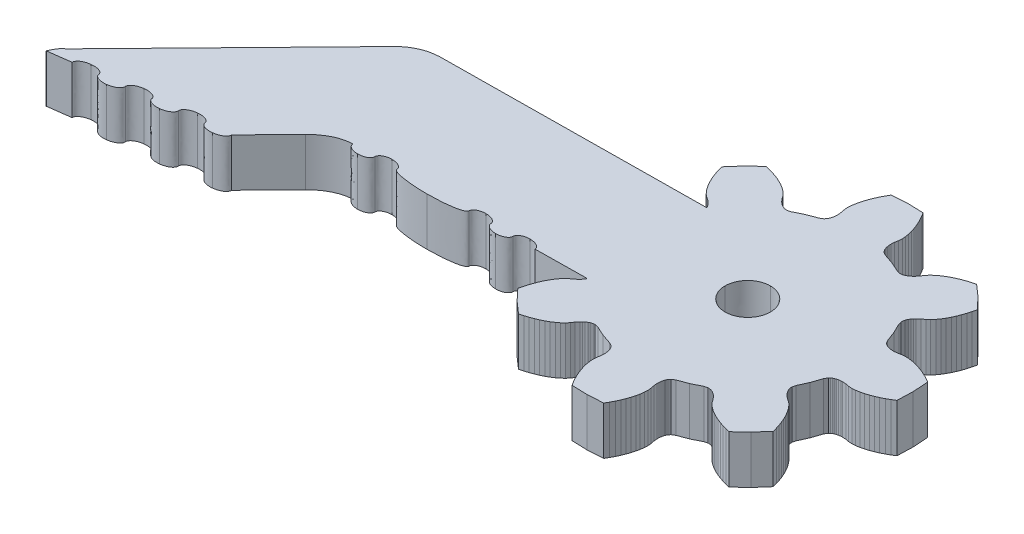
SolidWorks part; units mm, degrees
ref_plane "Front Plane" through (0, 0, 0) normal (0, 0, 1) x (1, 0, 0)
ref_plane "Top Plane" through (0, 0, 0) normal (0, 1, 0) x (1, 0, 0)
ref_plane "Right Plane" through (0, 0, 0) normal (1, 0, 0) x (0, 0, -1)
sketch "Sketch1" plane through (0, 0, 0) normal (0, 1, 0) x (1, 0, 0)
  line L1268 (81.0578, 158.2714) -> (81.0243, 158.3054)
  line L1269 (81.0243, 158.3054) -> (77.6477, 158.2613)
  line L1270 (63.4818, 157.2423) -> (61.064, 154.7634)
  line L1271 (51.6286, 153.6531) -> (50.1241, 153.4506)
  line L1272 (50.1241, 153.4506) -> (50.1273, 153.4248)
  line L1273 (50.5769, 154.1981) -> (50.6201, 154.1828)
  line L1274 (50.6201, 154.1828) -> (61.3822, 165.2167)
  line L1275 (61.3822, 165.2167) -> (61.3857, 165.2182)
  line L1276 (63.4907, 166.1354) -> (80.9763, 166.3177)
  line L1277 (80.9763, 166.3177) -> (80.9618, 166.3272)
  line L1278 (80.9618, 166.3272) -> (80.9303, 166.3857)
  line L1279 (80.9303, 166.3857) -> (80.8605, 166.4907)
  line L1280 (80.8605, 166.4907) -> (80.7838, 166.5839)
  line L1281 (80.7838, 166.5839) -> (80.7017, 166.668)
  line L1282 (80.7017, 166.668) -> (80.5246, 166.8149)
  line L1283 (80.5246, 166.8149) -> (80.3334, 166.9392)
  line L1284 (80.3334, 166.9392) -> (80.1557, 167.0849)
  line L1285 (80.1557, 167.0849) -> (79.9967, 167.2599)
  line L1286 (79.9967, 167.2599) -> (79.8501, 167.4532)
  line L1287 (79.8501, 167.4532) -> (79.7145, 167.6617)
  line L1288 (79.7145, 167.6617) -> (79.5894, 167.8837)
  line L1289 (79.5894, 167.8837) -> (79.4745, 168.1179)
  line L1290 (79.4745, 168.1179) -> (79.3699, 168.3635)
  line L1291 (79.3699, 168.3635) -> (79.2754, 168.6197)
  line L1292 (79.2754, 168.6197) -> (79.1915, 168.886)
  line L1293 (79.1915, 168.886) -> (79.1181, 169.1617)
  line L1294 (79.1181, 169.1617) -> (79.8009, 169.9374)
  line L1295 (79.8009, 169.9374) -> (80.5548, 170.6443)
  line L1296 (80.5548, 170.6443) -> (80.8327, 170.5796)
  line L1297 (80.8327, 170.5796) -> (81.1014, 170.504)
  line L1298 (81.1014, 170.504) -> (81.3605, 170.4177)
  line L1299 (81.3605, 170.4177) -> (81.6093, 170.3208)
  line L1300 (81.6093, 170.3208) -> (81.847, 170.2133)
  line L1301 (81.847, 170.2133) -> (82.0728, 170.0952)
  line L1302 (82.0728, 170.0952) -> (82.2854, 169.9663)
  line L1303 (82.2854, 169.9663) -> (82.4832, 169.8259)
  line L1304 (82.4832, 169.8259) -> (82.6631, 169.6724)
  line L1305 (82.6631, 169.6724) -> (82.8144, 169.4994)
  line L1306 (82.8144, 169.4994) -> (82.9446, 169.3122)
  line L1307 (82.9446, 169.3122) -> (83.097, 169.1398)
  line L1308 (83.097, 169.1398) -> (83.1836, 169.0603)
  line L1309 (83.1836, 169.0603) -> (83.2792, 168.9866)
  line L1310 (83.2792, 168.9866) -> (83.3864, 168.9201)
  line L1311 (83.3864, 168.9201) -> (83.4458, 168.8905)
  line L1312 (83.4458, 168.8905) -> (83.5105, 168.8639)
  line L1313 (83.5105, 168.8639) -> (83.5824, 168.8415)
  line L1314 (83.5824, 168.8415) -> (83.6651, 168.8253)
  line L1315 (83.6651, 168.8253) -> (83.768, 168.8205)
  line L1316 (83.768, 168.8205) -> (83.9876, 168.8804)
  line L1317 (83.9876, 168.8804) -> (84.6212, 169.1914)
  line L1318 (84.6212, 169.1914) -> (85.2815, 169.4403)
  line L1319 (85.2815, 169.4403) -> (85.4756, 169.5595)
  line L1320 (85.4756, 169.5595) -> (85.5425, 169.6378)
  line L1321 (85.5425, 169.6378) -> (85.5873, 169.7091)
  line L1322 (85.5873, 169.7091) -> (85.6202, 169.7768)
  line L1323 (85.6202, 169.7768) -> (85.6451, 169.8422)
  line L1324 (85.6451, 169.8422) -> (85.6641, 169.9058)
  line L1325 (85.6641, 169.9058) -> (85.6891, 170.0295)
  line L1326 (85.6891, 170.0295) -> (85.7007, 170.1496)
  line L1327 (85.7007, 170.1496) -> (85.7022, 170.2671)
  line L1328 (85.7022, 170.2671) -> (85.6808, 170.4962)
  line L1329 (85.6808, 170.4962) -> (85.6334, 170.7193)
  line L1330 (85.6334, 170.7193) -> (85.6109, 170.948)
  line L1331 (85.6109, 170.948) -> (85.6222, 171.1842)
  line L1332 (85.6222, 171.1842) -> (85.6552, 171.4245)
  line L1333 (85.6552, 171.4245) -> (85.7068, 171.6678)
  line L1334 (85.7068, 171.6678) -> (85.7752, 171.9132)
  line L1335 (85.7752, 171.9132) -> (85.8596, 172.1601)
  line L1336 (85.8596, 172.1601) -> (85.9593, 172.4078)
  line L1337 (85.9593, 172.4078) -> (86.0737, 172.6557)
  line L1338 (86.0737, 172.6557) -> (86.2026, 172.9034)
  line L1339 (86.2026, 172.9034) -> (86.3457, 173.1502)
  line L1340 (86.3457, 173.1502) -> (87.377, 173.2159)
  line L1341 (87.377, 173.2159) -> (88.4099, 173.1826)
  line L1342 (88.4099, 173.1826) -> (88.5607, 172.9404)
  line L1343 (88.5607, 172.9404) -> (88.6973, 172.6969)
  line L1344 (88.6973, 172.6969) -> (88.8195, 172.4527)
  line L1345 (88.8195, 172.4527) -> (88.9268, 172.2082)
  line L1346 (88.9268, 172.2082) -> (89.0189, 171.9642)
  line L1347 (89.0189, 171.9642) -> (89.0951, 171.721)
  line L1348 (89.0951, 171.721) -> (89.1543, 171.4795)
  line L1349 (89.1543, 171.4795) -> (89.1948, 171.2403)
  line L1350 (89.1948, 171.2403) -> (89.2136, 171.0046)
  line L1351 (89.2136, 171.0046) -> (89.1981, 170.7753)
  line L1352 (89.1981, 170.7753) -> (89.1579, 170.5508)
  line L1353 (89.1579, 170.5508) -> (89.1437, 170.3212)
  line L1354 (89.1437, 170.3212) -> (89.1488, 170.2038)
  line L1355 (89.1488, 170.2038) -> (89.1642, 170.0841)
  line L1356 (89.1642, 170.0841) -> (89.193, 169.9613)
  line L1357 (89.193, 169.9613) -> (89.214, 169.8982)
  line L1358 (89.214, 169.8982) -> (89.241, 169.8337)
  line L1359 (89.241, 169.8337) -> (89.276, 169.7671)
  line L1360 (89.276, 169.7671) -> (89.3231, 169.6971)
  line L1361 (89.3231, 169.6971) -> (89.3924, 169.621)
  line L1362 (89.3924, 169.621) -> (89.59, 169.508)
  line L1363 (89.59, 169.508) -> (90.2579, 169.28)
  line L1364 (90.2579, 169.28) -> (90.9009, 168.989)
  line L1365 (90.9009, 168.989) -> (91.1223, 168.9361)
  line L1366 (91.1223, 168.9361) -> (91.225, 168.9441)
  line L1367 (91.225, 168.9441) -> (91.3072, 168.9629)
  line L1368 (91.3072, 168.9629) -> (91.3783, 168.9875)
  line L1369 (91.3783, 168.9875) -> (91.4422, 169.0161)
  line L1370 (91.4422, 169.0161) -> (91.5006, 169.0476)
  line L1371 (91.5006, 169.0476) -> (91.6057, 169.1174)
  line L1372 (91.6057, 169.1174) -> (91.6989, 169.1941)
  line L1373 (91.6989, 169.1941) -> (91.7829, 169.2762)
  line L1374 (91.7829, 169.2762) -> (91.9298, 169.4533)
  line L1375 (91.9298, 169.4533) -> (92.0541, 169.6445)
  line L1376 (92.0541, 169.6445) -> (92.1999, 169.8223)
  line L1377 (92.1999, 169.8223) -> (92.3749, 169.9812)
  line L1378 (92.3749, 169.9812) -> (92.5682, 170.1278)
  line L1379 (92.5682, 170.1278) -> (92.7767, 170.2634)
  line L1380 (92.7767, 170.2634) -> (92.9986, 170.3885)
  line L1381 (92.9986, 170.3885) -> (93.2328, 170.5034)
  line L1382 (93.2328, 170.5034) -> (93.4784, 170.6081)
  line L1383 (93.4784, 170.6081) -> (93.7347, 170.7025)
  line L1384 (93.7347, 170.7025) -> (94.001, 170.7864)
  line L1385 (94.001, 170.7864) -> (94.2766, 170.8598)
  line L1386 (94.2766, 170.8598) -> (95.0524, 170.177)
  line L1387 (95.0524, 170.177) -> (95.7592, 169.4231)
  line L1388 (95.7592, 169.4231) -> (95.6945, 169.1453)
  line L1389 (95.6945, 169.1453) -> (95.6189, 168.8765)
  line L1390 (95.6189, 168.8765) -> (95.5327, 168.6174)
  line L1391 (95.5327, 168.6174) -> (95.4357, 168.3686)
  line L1392 (95.4357, 168.3686) -> (95.3283, 168.1309)
  line L1393 (95.3283, 168.1309) -> (95.2102, 167.9051)
  line L1394 (95.2102, 167.9051) -> (95.0812, 167.6925)
  line L1395 (95.0812, 167.6925) -> (94.9408, 167.4947)
  line L1396 (94.9408, 167.4947) -> (94.7874, 167.3148)
  line L1397 (94.7874, 167.3148) -> (94.6144, 167.1635)
  line L1398 (94.6144, 167.1635) -> (94.4271, 167.0333)
  line L1399 (94.4271, 167.0333) -> (94.2547, 166.8809)
  line L1400 (94.2547, 166.8809) -> (94.1753, 166.7943)
  line L1401 (94.1753, 166.7943) -> (94.1016, 166.6988)
  line L1402 (94.1016, 166.6988) -> (94.0351, 166.5915)
  line L1403 (94.0351, 166.5915) -> (94.0054, 166.5321)
  line L1404 (94.0054, 166.5321) -> (93.9788, 166.4674)
  line L1405 (93.9788, 166.4674) -> (93.9565, 166.3955)
  line L1406 (93.9565, 166.3955) -> (93.9403, 166.3128)
  line L1407 (93.9403, 166.3128) -> (93.9355, 166.21)
  line L1408 (93.9355, 166.21) -> (93.9954, 165.9903)
  line L1409 (93.9954, 165.9903) -> (94.3064, 165.3568)
  line L1410 (94.3064, 165.3568) -> (94.5553, 164.6964)
  line L1411 (94.5553, 164.6964) -> (94.6744, 164.5024)
  line L1412 (94.6744, 164.5024) -> (94.7527, 164.4354)
  line L1413 (94.7527, 164.4354) -> (94.824, 164.3906)
  line L1414 (94.824, 164.3906) -> (94.8918, 164.3578)
  line L1415 (94.8918, 164.3578) -> (94.9571, 164.3328)
  line L1416 (94.9571, 164.3328) -> (95.0208, 164.3138)
  line L1417 (95.0208, 164.3138) -> (95.1444, 164.2888)
  line L1418 (95.1444, 164.2888) -> (95.2645, 164.2772)
  line L1419 (95.2645, 164.2772) -> (95.382, 164.2758)
  line L1420 (95.382, 164.2758) -> (95.6112, 164.2972)
  line L1421 (95.6112, 164.2972) -> (95.8342, 164.3445)
  line L1422 (95.8342, 164.3445) -> (96.063, 164.3671)
  line L1423 (96.063, 164.3671) -> (96.2992, 164.3557)
  line L1424 (96.2992, 164.3557) -> (96.5395, 164.3227)
  line L1425 (96.5395, 164.3227) -> (96.7828, 164.2712)
  line L1426 (96.7828, 164.2712) -> (97.0282, 164.2027)
  line L1427 (97.0282, 164.2027) -> (97.275, 164.1183)
  line L1428 (97.275, 164.1183) -> (97.5227, 164.0186)
  line L1429 (97.5227, 164.0186) -> (97.7707, 163.9042)
  line L1430 (97.7707, 163.9042) -> (98.0183, 163.7753)
  line L1431 (98.0183, 163.7753) -> (98.2652, 163.6323)
  line L1432 (98.2652, 163.6323) -> (98.3308, 162.6009)
  line L1433 (98.3308, 162.6009) -> (98.2976, 161.568)
  line L1434 (98.2976, 161.568) -> (98.0554, 161.4173)
  line L1435 (98.0554, 161.4173) -> (97.8119, 161.2806)
  line L1436 (97.8119, 161.2806) -> (97.5677, 161.1585)
  line L1437 (97.5677, 161.1585) -> (97.3232, 161.0511)
  line L1438 (97.3232, 161.0511) -> (97.0791, 160.959)
  line L1439 (97.0791, 160.959) -> (96.836, 160.8829)
  line L1440 (96.836, 160.8829) -> (96.5944, 160.8237)
  line L1441 (96.5944, 160.8237) -> (96.3553, 160.7831)
  line L1442 (96.3553, 160.7831) -> (96.1196, 160.7644)
  line L1443 (96.1196, 160.7644) -> (95.8903, 160.7798)
  line L1444 (95.8903, 160.7798) -> (95.6658, 160.8201)
  line L1445 (95.6658, 160.8201) -> (95.4361, 160.8342)
  line L1446 (95.4361, 160.8342) -> (95.3187, 160.8291)
  line L1447 (95.3187, 160.8291) -> (95.199, 160.8137)
  line L1448 (95.199, 160.8137) -> (95.0762, 160.7849)
  line L1449 (95.0762, 160.7849) -> (95.0132, 160.7639)
  line L1450 (95.0132, 160.7639) -> (94.9487, 160.7369)
  line L1451 (94.9487, 160.7369) -> (94.882, 160.7019)
  line L1452 (94.882, 160.7019) -> (94.8121, 160.6549)
  line L1453 (94.8121, 160.6549) -> (94.736, 160.5855)
  line L1454 (94.736, 160.5855) -> (94.623, 160.3879)
  line L1455 (94.623, 160.3879) -> (94.3949, 159.72)
  line L1456 (94.3949, 159.72) -> (94.1039, 159.077)
  line L1457 (94.1039, 159.077) -> (94.051, 158.8556)
  line L1458 (94.051, 158.8556) -> (94.0591, 158.7529)
  line L1459 (94.0591, 158.7529) -> (94.0778, 158.6708)
  line L1460 (94.0778, 158.6708) -> (94.1025, 158.5996)
  line L1461 (94.1025, 158.5996) -> (94.131, 158.5358)
  line L1462 (94.131, 158.5358) -> (94.1626, 158.4773)
  line L1463 (94.1626, 158.4773) -> (94.2324, 158.3722)
  line L1464 (94.2324, 158.3722) -> (94.3091, 158.2791)
  line L1465 (94.3091, 158.2791) -> (94.3912, 158.195)
  line L1466 (94.3912, 158.195) -> (94.5683, 158.0481)
  line L1467 (94.5683, 158.0481) -> (94.7595, 157.9238)
  line L1468 (94.7595, 157.9238) -> (94.9372, 157.778)
  line L1469 (94.9372, 157.778) -> (95.0962, 157.603)
  line L1470 (95.0962, 157.603) -> (95.2427, 157.4097)
  line L1471 (95.2427, 157.4097) -> (95.3783, 157.2013)
  line L1472 (95.3783, 157.2013) -> (95.5035, 156.9793)
  line L1473 (95.5035, 156.9793) -> (95.6184, 156.7451)
  line L1474 (95.6184, 156.7451) -> (95.723, 156.4995)
  line L1475 (95.723, 156.4995) -> (95.8174, 156.2432)
  line L1476 (95.8174, 156.2432) -> (95.9014, 155.9769)
  line L1477 (95.9014, 155.9769) -> (95.9748, 155.7013)
  line L1478 (95.9748, 155.7013) -> (95.292, 154.9255)
  line L1479 (95.292, 154.9255) -> (94.5381, 154.2187)
  line L1480 (94.5381, 154.2187) -> (94.2602, 154.2834)
  line L1481 (94.2602, 154.2834) -> (93.9914, 154.359)
  line L1482 (93.9914, 154.359) -> (93.7324, 154.4453)
  line L1483 (93.7324, 154.4453) -> (93.4836, 154.5422)
  line L1484 (93.4836, 154.5422) -> (93.2458, 154.6496)
  line L1485 (93.2458, 154.6496) -> (93.0201, 154.7677)
  line L1486 (93.0201, 154.7677) -> (92.8074, 154.8967)
  line L1487 (92.8074, 154.8967) -> (92.6097, 155.0371)
  line L1488 (92.6097, 155.0371) -> (92.4297, 155.1905)
  line L1489 (92.4297, 155.1905) -> (92.2785, 155.3636)
  line L1490 (92.2785, 155.3636) -> (92.1482, 155.5508)
  line L1491 (92.1482, 155.5508) -> (91.9959, 155.7232)
  line L1492 (91.9959, 155.7232) -> (91.9092, 155.8026)
  line L1493 (91.9092, 155.8026) -> (91.8137, 155.8763)
  line L1494 (91.8137, 155.8763) -> (91.7065, 155.9428)
  line L1495 (91.7065, 155.9428) -> (91.6471, 155.9725)
  line L1496 (91.6471, 155.9725) -> (91.5824, 155.9991)
  line L1497 (91.5824, 155.9991) -> (91.5105, 156.0215)
  line L1498 (91.5105, 156.0215) -> (91.4278, 156.0376)
  line L1499 (91.4278, 156.0376) -> (91.3249, 156.0424)
  line L1500 (91.3249, 156.0424) -> (91.1052, 155.9826)
  line L1501 (91.1052, 155.9826) -> (90.4717, 155.6716)
  line L1502 (90.4717, 155.6716) -> (89.8113, 155.4226)
  line L1503 (89.8113, 155.4226) -> (89.6173, 155.3035)
  line L1504 (89.6173, 155.3035) -> (89.5504, 155.2252)
  line L1505 (89.5504, 155.2252) -> (89.5056, 155.1539)
  line L1506 (89.5056, 155.1539) -> (89.4727, 155.0862)
  line L1507 (89.4727, 155.0862) -> (89.4478, 155.0208)
  line L1508 (89.4478, 155.0208) -> (89.4287, 154.9571)
  line L1509 (89.4287, 154.9571) -> (89.4038, 154.8335)
  line L1510 (89.4038, 154.8335) -> (89.3921, 154.7134)
  line L1511 (89.3921, 154.7134) -> (89.3907, 154.5959)
  line L1512 (89.3907, 154.5959) -> (89.4121, 154.3667)
  line L1513 (89.4121, 154.3667) -> (89.4594, 154.1437)
  line L1514 (89.4594, 154.1437) -> (89.482, 153.9149)
  line L1515 (89.482, 153.9149) -> (89.4707, 153.6788)
  line L1516 (89.4707, 153.6788) -> (89.4377, 153.4385)
  line L1517 (89.4377, 153.4385) -> (89.3861, 153.1952)
  line L1518 (89.3861, 153.1952) -> (89.3176, 152.9497)
  line L1519 (89.3176, 152.9497) -> (89.2332, 152.7029)
  line L1520 (89.2332, 152.7029) -> (89.1336, 152.4552)
  line L1521 (89.1336, 152.4552) -> (89.0191, 152.2072)
  line L1522 (89.0191, 152.2072) -> (88.8903, 151.9596)
  line L1523 (88.8903, 151.9596) -> (88.7472, 151.7128)
  line L1524 (88.7472, 151.7128) -> (87.7159, 151.6471)
  line L1525 (87.7159, 151.6471) -> (86.6829, 151.6804)
  line L1526 (86.6829, 151.6804) -> (86.5322, 151.9226)
  line L1527 (86.5322, 151.9226) -> (86.3956, 152.166)
  line L1528 (86.3956, 152.166) -> (86.2734, 152.4103)
  line L1529 (86.2734, 152.4103) -> (86.166, 152.6547)
  line L1530 (86.166, 152.6547) -> (86.0739, 152.8988)
  line L1531 (86.0739, 152.8988) -> (85.9978, 153.1419)
  line L1532 (85.9978, 153.1419) -> (85.9386, 153.3835)
  line L1533 (85.9386, 153.3835) -> (85.8981, 153.6226)
  line L1534 (85.8981, 153.6226) -> (85.8793, 153.8584)
  line L1535 (85.8793, 153.8584) -> (85.8947, 154.0877)
  line L1536 (85.8947, 154.0877) -> (85.935, 154.3121)
  line L1537 (85.935, 154.3121) -> (85.9492, 154.5418)
  line L1538 (85.9492, 154.5418) -> (85.9441, 154.6592)
  line L1539 (85.9441, 154.6592) -> (85.9287, 154.7789)
  line L1540 (85.9287, 154.7789) -> (85.8999, 154.9017)
  line L1541 (85.8999, 154.9017) -> (85.8788, 154.9647)
  line L1542 (85.8788, 154.9647) -> (85.8518, 155.0293)
  line L1543 (85.8518, 155.0293) -> (85.8168, 155.0959)
  line L1544 (85.8168, 155.0959) -> (85.7698, 155.1658)
  line L1545 (85.7698, 155.1658) -> (85.7005, 155.242)
  line L1546 (85.7005, 155.242) -> (85.5028, 155.3549)
  line L1547 (85.5028, 155.3549) -> (84.8349, 155.583)
  line L1548 (84.8349, 155.583) -> (84.1919, 155.874)
  line L1549 (84.1919, 155.874) -> (83.9705, 155.9269)
  line L1550 (83.9705, 155.9269) -> (83.8679, 155.9189)
  line L1551 (83.8679, 155.9189) -> (83.7857, 155.9001)
  line L1552 (83.7857, 155.9001) -> (83.7146, 155.8755)
  line L1553 (83.7146, 155.8755) -> (83.6507, 155.8469)
  line L1554 (83.6507, 155.8469) -> (83.5922, 155.8153)
  line L1555 (83.5922, 155.8153) -> (83.4872, 155.7456)
  line L1556 (83.4872, 155.7456) -> (83.394, 155.6689)
  line L1557 (83.394, 155.6689) -> (83.3099, 155.5868)
  line L1558 (83.3099, 155.5868) -> (83.163, 155.4096)
  line L1559 (83.163, 155.4096) -> (83.0388, 155.2184)
  line L1560 (83.0388, 155.2184) -> (82.893, 155.0407)
  line L1561 (82.893, 155.0407) -> (82.718, 154.8817)
  line L1562 (82.718, 154.8817) -> (82.5247, 154.7352)
  line L1563 (82.5247, 154.7352) -> (82.3162, 154.5996)
  line L1564 (82.3162, 154.5996) -> (82.0943, 154.4745)
  line L1565 (82.0943, 154.4745) -> (81.86, 154.3596)
  line L1566 (81.86, 154.3596) -> (81.6144, 154.2549)
  line L1567 (81.6144, 154.2549) -> (81.3582, 154.1605)
  line L1568 (81.3582, 154.1605) -> (81.0919, 154.0765)
  line L1569 (81.0919, 154.0765) -> (80.8162, 154.0031)
  line L1570 (80.8162, 154.0031) -> (80.0405, 154.686)
  line L1571 (80.0405, 154.686) -> (79.3336, 155.4399)
  line L1572 (79.3336, 155.4399) -> (79.3983, 155.7177)
  line L1573 (79.3983, 155.7177) -> (79.4739, 155.9865)
  line L1574 (79.4739, 155.9865) -> (79.5602, 156.2456)
  line L1575 (79.5602, 156.2456) -> (79.6571, 156.4943)
  line L1576 (79.6571, 156.4943) -> (79.7646, 156.7321)
  line L1577 (79.7646, 156.7321) -> (79.8827, 156.9578)
  line L1578 (79.8827, 156.9578) -> (80.0116, 157.1705)
  line L1579 (80.0116, 157.1705) -> (80.1521, 157.3682)
  line L1580 (80.1521, 157.3682) -> (80.3055, 157.5482)
  line L1581 (80.3055, 157.5482) -> (80.4785, 157.6995)
  line L1582 (80.4785, 157.6995) -> (80.6657, 157.8297)
  line L1583 (80.6657, 157.8297) -> (80.8382, 157.9821)
  line L1584 (80.8382, 157.9821) -> (80.9176, 158.0687)
  line L1585 (80.9176, 158.0687) -> (80.9913, 158.1642)
  line L1586 (80.9913, 158.1642) -> (81.0578, 158.2714)
  spline S1574 degree 3 poles (77.6477, 158.2613) (77.6445, 158.4894) (77.3152, 158.6743) (76.9123, 158.6743) knots 0.005764 0.005764 0.005764 0.005764 0.008646 0.008646 0.008646 0.008646
  spline S1575 degree 3 poles (76.9123, 158.6743) (76.5093, 158.6743) (76.1853, 158.4894) (76.1885, 158.2613) knots 0.008646 0.008646 0.008646 0.008646 0.011527 0.011527 0.011527 0.011527
  spline S1576 degree 3 poles (76.1885, 158.2613) (76.1916, 158.0332) (75.8676, 157.8483) (75.4646, 157.8483) knots 0.011527 0.011527 0.011527 0.011527 0.014409 0.014409 0.014409 0.014409
  spline S1577 degree 3 poles (75.4646, 157.8483) (75.0617, 157.8483) (74.7324, 158.0332) (74.7292, 158.2613) knots 0.014409 0.014409 0.014409 0.014409 0.017291 0.017291 0.017291 0.017291
  spline S1578 degree 3 poles (74.7292, 158.2613) (74.7259, 158.4894) (74.3967, 158.6743) (73.9937, 158.6743) knots 0.017291 0.017291 0.017291 0.017291 0.020173 0.020173 0.020173 0.020173
  spline S1579 degree 3 poles (73.9937, 158.6743) (73.5908, 158.6743) (73.2667, 158.4894) (73.2697, 158.2613) knots 0.020173 0.020173 0.020173 0.020173 0.023055 0.023055 0.023055 0.023055
  spline S1580 degree 3 poles (73.2697, 158.2613) (73.28, 158.0331) (72.2231, 157.8482) (70.909, 157.8482) knots 0.023055 0.023055 0.023055 0.023055 0.025937 0.025937 0.025937 0.025937
  spline S1581 degree 3 poles (70.909, 157.8482) (69.5949, 157.8482) (68.5211, 158.0331) (68.5107, 158.2613) knots 0.025937 0.025937 0.025937 0.025937 0.028818 0.028818 0.028818 0.028818
  spline S1582 degree 3 poles (68.5107, 158.2613) (68.5074, 158.4893) (68.1782, 158.6742) (67.7752, 158.6742) knots 0.028818 0.028818 0.028818 0.028818 0.0317 0.0317 0.0317 0.0317
  spline S1583 degree 3 poles (67.7752, 158.6742) (67.3723, 158.6742) (67.0482, 158.4893) (67.0514, 158.2612) knots 0.0317 0.0317 0.0317 0.0317 0.034582 0.034582 0.034582 0.034582
  spline S1584 degree 3 poles (67.0514, 158.2612) (67.0546, 158.0331) (66.7305, 157.8482) (66.3276, 157.8482) knots 0.034582 0.034582 0.034582 0.034582 0.037464 0.037464 0.037464 0.037464
  spline S1585 degree 3 poles (66.3276, 157.8482) (65.9246, 157.8482) (65.5954, 158.0331) (65.5922, 158.2612) knots 0.037464 0.037464 0.037464 0.037464 0.040346 0.040346 0.040346 0.040346
  spline S1586 degree 3 poles (65.5922, 158.2612) (64.7966, 158.2513) (64.0374, 157.8118) (63.4818, 157.2423) knots 0.040346 0.040346 0.040346 0.040346 0.043228 0.043228 0.043228 0.043228
  spline S1587 degree 3 poles (61.064, 154.7634) (61.0872, 154.5364) (60.754, 154.3111) (60.3198, 154.2599) knots 0.04611 0.04611 0.04611 0.04611 0.048991 0.048991 0.048991 0.048991
  spline S1588 degree 3 poles (60.3198, 154.2599) (59.8855, 154.2088) (59.5147, 154.3514) (59.4915, 154.5783) knots 0.048991 0.048991 0.048991 0.048991 0.051873 0.051873 0.051873 0.051873
  spline S1589 degree 3 poles (59.4915, 154.5783) (59.4682, 154.8053) (59.0974, 154.9478) (58.6632, 154.8967) knots 0.051873 0.051873 0.051873 0.051873 0.054755 0.054755 0.054755 0.054755
  spline S1590 degree 3 poles (58.6632, 154.8967) (58.2289, 154.8456) (57.8957, 154.6202) (57.9189, 154.3933) knots 0.054755 0.054755 0.054755 0.054755 0.057637 0.057637 0.057637 0.057637
  spline S1591 degree 3 poles (57.9189, 154.3933) (57.9421, 154.1664) (57.6089, 153.941) (57.1746, 153.8899) knots 0.057637 0.057637 0.057637 0.057637 0.060519 0.060519 0.060519 0.060519
  spline S1592 degree 3 poles (57.1746, 153.8899) (56.7404, 153.8388) (56.3695, 153.9813) (56.3463, 154.2083) knots 0.060519 0.060519 0.060519 0.060519 0.063401 0.063401 0.063401 0.063401
  spline S1593 degree 3 poles (56.3463, 154.2083) (56.3231, 154.4352) (55.9522, 154.5777) (55.518, 154.5266) knots 0.063401 0.063401 0.063401 0.063401 0.066282 0.066282 0.066282 0.066282
  spline S1594 degree 3 poles (55.518, 154.5266) (55.0837, 154.4755) (54.7505, 154.2501) (54.7738, 154.0232) knots 0.066282 0.066282 0.066282 0.066282 0.069164 0.069164 0.069164 0.069164
  spline S1595 degree 3 poles (54.7738, 154.0232) (54.7969, 153.7963) (54.4637, 153.5709) (54.0294, 153.5198) knots 0.069164 0.069164 0.069164 0.069164 0.072046 0.072046 0.072046 0.072046
  spline S1596 degree 3 poles (54.0294, 153.5198) (53.5952, 153.4687) (53.2244, 153.6112) (53.2012, 153.8382) knots 0.072046 0.072046 0.072046 0.072046 0.074928 0.074928 0.074928 0.074928
  spline S1597 degree 3 poles (53.2012, 153.8382) (53.1779, 154.0651) (52.8071, 154.2077) (52.3728, 154.1566) knots 0.074928 0.074928 0.074928 0.074928 0.07781 0.07781 0.07781 0.07781
  spline S1598 degree 3 poles (52.3728, 154.1566) (51.9386, 154.1054) (51.6054, 153.8801) (51.6286, 153.6531) knots 0.07781 0.07781 0.07781 0.07781 0.080692 0.080692 0.080692 0.080692
  spline S1599 degree 3 poles (50.1273, 153.4248) (50.0602, 153.424) (50.3443, 153.9596) (50.5769, 154.1981) knots 0.086455 0.086455 0.086455 0.086455 0.089337 0.089337 0.089337 0.089337
  spline S1600 degree 3 poles (61.3857, 165.2182) (61.938, 165.791) (62.6952, 166.1209) (63.4907, 166.1354) knots 0.097983 0.097983 0.097983 0.097983 0.100865 0.100865 0.100865 0.100865
  spline S1601 degree 3 poles (86.0463, 162.4441) (86.0463, 161.6157) (86.7179, 160.944) (87.5463, 160.944) knots 0 0 0 0 0.2 0.2 0.2 0.2
  spline S1602 degree 3 poles (87.5463, 160.944) (88.3747, 160.9439) (89.0464, 161.6157) (89.0464, 162.444) knots 0.2 0.2 0.2 0.2 0.4 0.4 0.4 0.4
  spline S1603 degree 3 poles (89.0464, 162.444) (89.0465, 163.2725) (88.3747, 163.9441) (87.5464, 163.9442) knots 0.4 0.4 0.4 0.4 0.6 0.6 0.6 0.6
  spline S1604 degree 3 poles (87.5464, 163.9442) (86.7179, 163.9442) (86.0463, 163.2725) (86.0463, 162.4441) knots 0.6 0.6 0.6 0.6 1 1 1 1
extrude "Boss-Extrude1" add sketch "Sketch1" along normal blind 3.175
